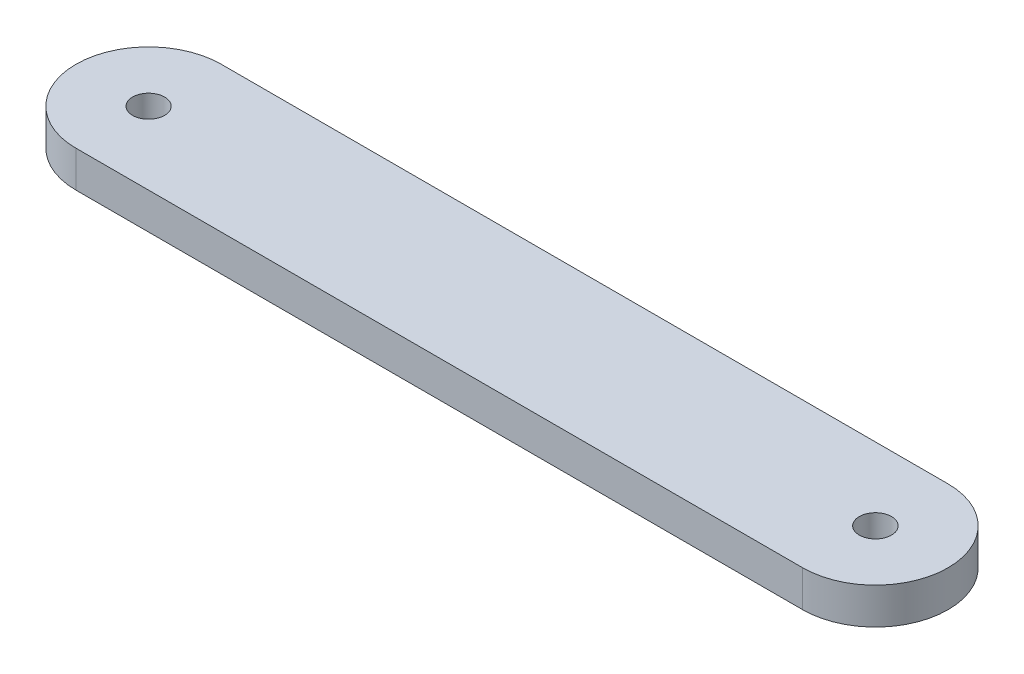
SolidWorks part; units mm, degrees
ref_plane "Front" through (0, 0, 0) normal (0, 0, 1) x (1, 0, 0)
ref_plane "Top" through (0, 0, 0) normal (0, 1, 0) x (1, 0, 0)
ref_plane "Right" through (0, 0, 0) normal (1, 0, 0) x (0, 0, -1)
sketch "Sketch1" plane through (0, 0, 0) normal (0, 1, 0) x (1, 0, 0)
  line L0 (0, 0) -> (127, 0) construction
  line L1 (0, 12.7) -> (127, 12.7)
  line L2 (0, -12.7) -> (127, -12.7)
  arc A0 (0, 12.7) -> (0, -12.7) centre (0, 0) ccw
  arc A1 (127, -12.7) -> (127, 12.7) centre (127, 0) ccw
  circle A2 centre (0, 0) radius 2.794
  circle A3 centre (127, 0) radius 2.8135
  point P3 (63.5, 0)
  dimension "D1" = 5.588
  dimension "D2" = 5.627
extrude "Boss-Extrude1" add sketch "Sketch1" along normal blind 6.35
